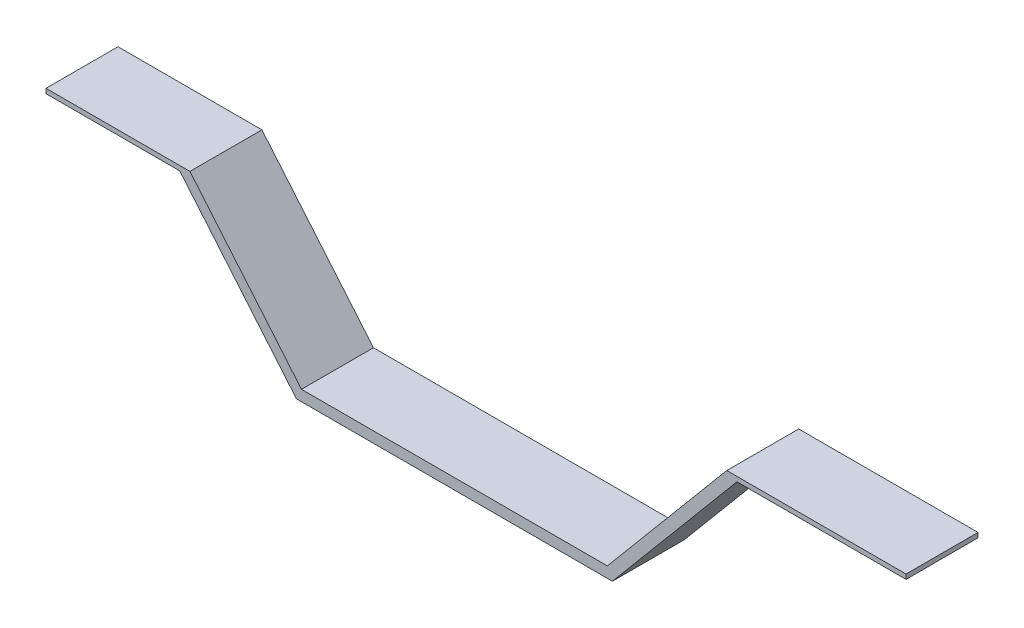
SolidWorks part; units mm, degrees
ref_plane "Front Plane" through (0, 0, 0) normal (0, 0, 1) x (1, 0, 0)
ref_plane "Top Plane" through (0, 0, 0) normal (0, 1, 0) x (1, 0, 0)
ref_plane "Right Plane" through (0, 0, 0) normal (1, 0, 0) x (0, 0, -1)
sketch "Sketch1" plane through (0, 0, 0) normal (0, 0, 1) x (1, 0, 0)
  line L0 (-176.9256, 29.589) -> (-136.9256, 29.589)
  line L1 (-136.9256, 29.589) -> (-105.9256, -7.3554)
  line L2 (-105.9256, -7.3554) -> (-20.9256, -7.3554)
  line L3 (62.0744, 32.1932) -> (12.2596, 32.1932)
  line L4 (-20.9256, -7.3554) -> (12.2596, 32.1932)
  line L5 (-63.4256, 66.1932) -> (-63.4256, -72.0417) construction
  line L6 (-176.9256, 28.289) -> (-139.751, 28.289)
  line L7 (-106.5318, -8.6554) -> (-20.3194, -8.6554) construction
  line L8 (-138.3245, 26.589) -> (-107.3245, -10.3554) construction
  line L9 (-19.5267, -10.3554) -> (13.6586, 29.1932) construction
  line L10 (62.0744, 30.8932) -> (15.085, 30.8932)
  line L11 (-176.9256, 28.289) -> (-137.5318, 28.289) construction
  line L12 (-139.751, 28.289) -> (-107.3245, -10.3554)
  line L13 (-107.3245, -10.3554) -> (-19.5267, -10.3554)
  line L14 (-19.5267, -10.3554) -> (15.085, 30.8932)
  line L15 (62.0744, 30.8932) -> (12.8658, 30.8932) construction
  line L16 (-176.9256, 26.589) -> (-138.3245, 26.589) construction
  line L17 (-137.5318, 28.289) -> (-106.5318, -8.6554) construction
  line L18 (-20.3194, -8.6554) -> (12.8658, 30.8932) construction
  line L19 (62.0744, 29.1932) -> (13.6586, 29.1932) construction
  line L20 (-176.9256, 29.589) -> (-176.9256, 28.289)
  line L21 (62.0744, 32.1932) -> (62.0744, 30.8932)
  point P6 (-63.4256, -7.3554)
  dimension "D1" = 40
  dimension "D2" = 239
  dimension "D3" = 1.3
  dimension "D4" = 3
extrude "Boss-Extrude1" add sketch "Sketch1" along normal blind 20
